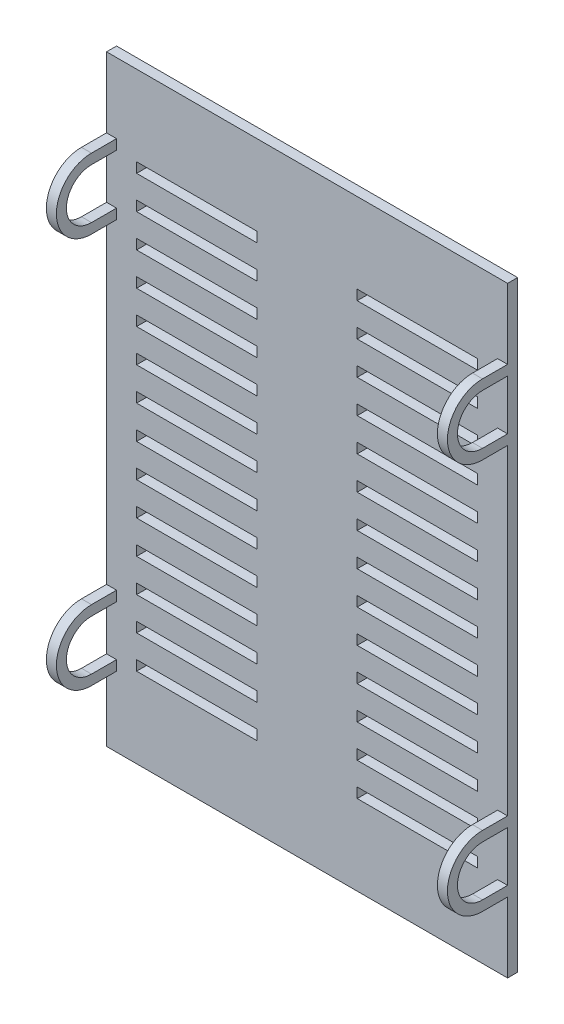
SolidWorks part; units mm, degrees
ref_plane "Alzado" through (0, 0, 0) normal (0, 0, 1) x (1, 0, 0)
ref_plane "Planta" through (0, 0, 0) normal (0, 1, 0) x (1, 0, 0)
ref_plane "Vista lateral" through (0, 0, 0) normal (1, 0, 0) x (0, 0, -1)
sketch "Croquis1" plane through (0, 0, 0) normal (0, 0, 1) x (1, 0, 0)
  line L1 (-100, -150) -> (100, -150)
  line L2 (-100, -150) -> (-100, 150)
  line L3 (-100, 150) -> (100, 150)
  line L4 (100, -150) -> (100, 150)
  line L5 (-100, -150) -> (100, 150) construction
  line L6 (-100, 150) -> (100, -150) construction
  point P0 (0, 0)
  dimension "D1" = 200
  dimension "D2" = 300
extrude "Saliente-Extruir1" add sketch "Croquis1" along normal blind 5
sketch "Croquis2" plane through (0, 0, 5) normal (0, 0, 1) x (1, 0, 0)
  line L0 (100, 150) -> (-100, 150) construction
  line L1 (-85, 110) -> (-25, 110)
  line L2 (-85, 110) -> (-85, 105)
  line L3 (-85, 105) -> (-25, 105)
  line L4 (-25, 110) -> (-25, 105)
  line L5 (-100, 150) -> (-100, -150) construction
  line L6 (25, 110) -> (85, 110)
  line L7 (25, 105) -> (85, 105)
  line L8 (85, 110) -> (85, 105)
  line L9 (25, 110) -> (25, 105)
  line L10 (25, 93.4615) -> (85, 93.4615)
  line L11 (25, 88.4615) -> (85, 88.4615)
  line L12 (85, 93.4615) -> (85, 88.4615)
  line L13 (25, 93.4615) -> (25, 88.4615)
  line L14 (25, 76.9231) -> (85, 76.9231)
  line L15 (25, 71.9231) -> (85, 71.9231)
  line L16 (85, 76.9231) -> (85, 71.9231)
  line L17 (25, 76.9231) -> (25, 71.9231)
  line L18 (25, 60.3846) -> (85, 60.3846)
  line L19 (25, 55.3846) -> (85, 55.3846)
  line L20 (85, 60.3846) -> (85, 55.3846)
  line L21 (25, 60.3846) -> (25, 55.3846)
  line L22 (25, 43.8462) -> (85, 43.8462)
  line L23 (25, 38.8462) -> (85, 38.8462)
  line L24 (85, 43.8462) -> (85, 38.8462)
  line L25 (25, 43.8462) -> (25, 38.8462)
  line L26 (25, 27.3077) -> (85, 27.3077)
  line L27 (25, 22.3077) -> (85, 22.3077)
  line L28 (85, 27.3077) -> (85, 22.3077)
  line L29 (25, 27.3077) -> (25, 22.3077)
  line L30 (25, 10.7692) -> (85, 10.7692)
  line L31 (25, 5.7692) -> (85, 5.7692)
  line L32 (85, 10.7692) -> (85, 5.7692)
  line L33 (25, 10.7692) -> (25, 5.7692)
  line L34 (25, -5.7692) -> (85, -5.7692)
  line L35 (25, -10.7692) -> (85, -10.7692)
  line L36 (85, -5.7692) -> (85, -10.7692)
  line L37 (25, -5.7692) -> (25, -10.7692)
  line L38 (25, -22.3077) -> (85, -22.3077)
  line L39 (25, -27.3077) -> (85, -27.3077)
  line L40 (85, -22.3077) -> (85, -27.3077)
  line L41 (25, -22.3077) -> (25, -27.3077)
  line L42 (25, -38.8462) -> (85, -38.8462)
  line L43 (25, -43.8462) -> (85, -43.8462)
  line L44 (85, -38.8462) -> (85, -43.8462)
  line L45 (25, -38.8462) -> (25, -43.8462)
  line L46 (25, -55.3846) -> (85, -55.3846)
  line L47 (25, -60.3846) -> (85, -60.3846)
  line L48 (85, -55.3846) -> (85, -60.3846)
  line L49 (25, -55.3846) -> (25, -60.3846)
  line L50 (25, -71.9231) -> (85, -71.9231)
  line L51 (25, -76.9231) -> (85, -76.9231)
  line L52 (85, -71.9231) -> (85, -76.9231)
  line L53 (25, -71.9231) -> (25, -76.9231)
  line L54 (25, -88.4615) -> (85, -88.4615)
  line L55 (25, -93.4615) -> (85, -93.4615)
  line L56 (85, -88.4615) -> (85, -93.4615)
  line L57 (25, -88.4615) -> (25, -93.4615)
  line L58 (25, -105) -> (85, -105)
  line L59 (25, -110) -> (85, -110)
  line L60 (85, -105) -> (85, -110)
  line L61 (25, -105) -> (25, -110)
  line L62 (-85, 93.4615) -> (-25, 93.4615)
  line L63 (-85, 88.4615) -> (-25, 88.4615)
  line L64 (-25, 93.4615) -> (-25, 88.4615)
  line L65 (-85, 93.4615) -> (-85, 88.4615)
  line L66 (-85, 76.9231) -> (-25, 76.9231)
  line L67 (-85, 71.9231) -> (-25, 71.9231)
  line L68 (-25, 76.9231) -> (-25, 71.9231)
  line L69 (-85, 76.9231) -> (-85, 71.9231)
  line L70 (-85, 60.3846) -> (-25, 60.3846)
  line L71 (-85, 55.3846) -> (-25, 55.3846)
  line L72 (-25, 60.3846) -> (-25, 55.3846)
  line L73 (-85, 60.3846) -> (-85, 55.3846)
  line L74 (-85, 43.8462) -> (-25, 43.8462)
  line L75 (-85, 38.8462) -> (-25, 38.8462)
  line L76 (-25, 43.8462) -> (-25, 38.8462)
  line L77 (-85, 43.8462) -> (-85, 38.8462)
  line L78 (-85, 27.3077) -> (-25, 27.3077)
  line L79 (-85, 22.3077) -> (-25, 22.3077)
  line L80 (-25, 27.3077) -> (-25, 22.3077)
  line L81 (-85, 27.3077) -> (-85, 22.3077)
  line L82 (-85, 10.7692) -> (-25, 10.7692)
  line L83 (-85, 5.7692) -> (-25, 5.7692)
  line L84 (-25, 10.7692) -> (-25, 5.7692)
  line L85 (-85, 10.7692) -> (-85, 5.7692)
  line L86 (-85, -5.7692) -> (-25, -5.7692)
  line L87 (-85, -10.7692) -> (-25, -10.7692)
  line L88 (-25, -5.7692) -> (-25, -10.7692)
  line L89 (-85, -5.7692) -> (-85, -10.7692)
  line L90 (-85, -22.3077) -> (-25, -22.3077)
  line L91 (-85, -27.3077) -> (-25, -27.3077)
  line L92 (-25, -22.3077) -> (-25, -27.3077)
  line L93 (-85, -22.3077) -> (-85, -27.3077)
  line L94 (-85, -38.8462) -> (-25, -38.8462)
  line L95 (-85, -43.8462) -> (-25, -43.8462)
  line L96 (-25, -38.8462) -> (-25, -43.8462)
  line L97 (-85, -38.8462) -> (-85, -43.8462)
  line L98 (-85, -55.3846) -> (-25, -55.3846)
  line L99 (-85, -60.3846) -> (-25, -60.3846)
  line L100 (-25, -55.3846) -> (-25, -60.3846)
  line L101 (-85, -55.3846) -> (-85, -60.3846)
  line L102 (-85, -71.9231) -> (-25, -71.9231)
  line L103 (-85, -76.9231) -> (-25, -76.9231)
  line L104 (-25, -71.9231) -> (-25, -76.9231)
  line L105 (-85, -71.9231) -> (-85, -76.9231)
  line L106 (-85, -88.4615) -> (-25, -88.4615)
  line L107 (-85, -93.4615) -> (-25, -93.4615)
  line L108 (-25, -88.4615) -> (-25, -93.4615)
  line L109 (-85, -88.4615) -> (-85, -93.4615)
  line L110 (-85, -105) -> (-25, -105)
  line L111 (-85, -110) -> (-25, -110)
  line L112 (-25, -105) -> (-25, -110)
  line L113 (-85, -105) -> (-85, -110)
  line L114 (-100, -150) -> (100, -150) construction
  line L115 (100, -150) -> (100, 150) construction
  dimension "D1" = 60
  dimension "D2" = 5
  dimension "D3" = 40
  dimension "D4" = 15
  dimension "D5" = 2
  dimension "D7" = 40
  dimension "D8" = 15
  dimension "D6" = 14
extrude "Cortar-Extruir1" cut sketch "Croquis2" against normal through all
sketch "Croquis5" plane through (-100, 0, 0) normal (-1, 0, 0) x (0, 0, 1)
  line L1 (5, 150) -> (5, -150) construction
  line L2 (17.5, 110) -> (5, 110)
  line L3 (17.5, 85) -> (5, 85)
  line L4 (17.5, -85) -> (5, -85)
  line L5 (17.5, -110) -> (5, -110)
  arc A2 (17.5, 85) -> (17.5, 110) centre (17.5, 97.5) ccw
  arc A3 (17.5, -110) -> (17.5, -85) centre (17.5, -97.5) ccw
  point P22 (0, 0)
  point P23 (0, 0)
  dimension "D1" = 25
  dimension "D3" = 40
  dimension "D4" = 40
  dimension "D2" = 2
extrude "Extruir-Lámina1" add sketch "Croquis5" against normal blind 200 thin
sketch "Croquis7" plane through (0, 0, 5) normal (0, 0, 1) x (1, 0, 0)
  line L0 (-100, 150) -> (-100, 115) construction
  line L1 (-95, 144.7909) -> (95, 144.7909)
  line L2 (-95, 144.7909) -> (-95, -127.5092)
  line L3 (-95, -127.5092) -> (95, -127.5092)
  line L4 (95, 144.7909) -> (95, -127.5092)
  line L5 (100, 115) -> (100, 150) construction
  dimension "D1" = 5
  dimension "D2" = 5
extrude "Cortar-Extruir2" cut sketch "Croquis7" along normal through all
